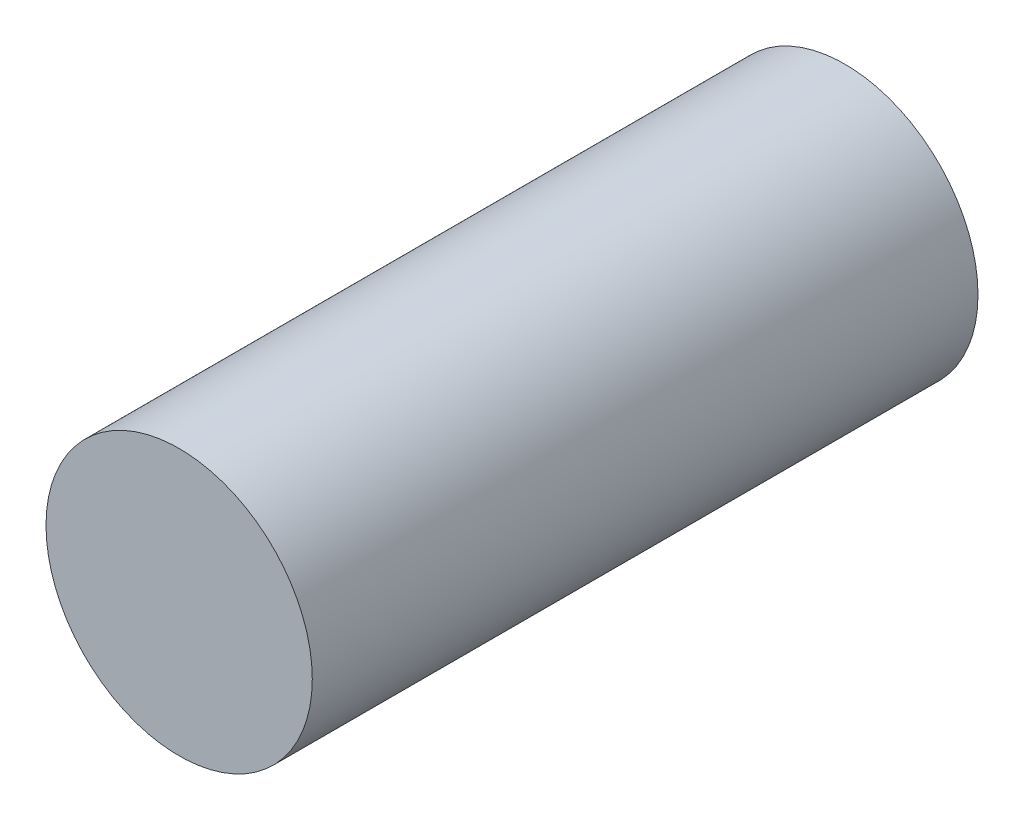
SolidWorks part; units mm, degrees
ref_plane "Plan de face" through (0, 0, 0) normal (0, 0, 1) x (1, 0, 0)
ref_plane "Plan de dessus" through (0, 0, 0) normal (0, 1, 0) x (1, 0, 0)
ref_plane "Plan de droite" through (0, 0, 0) normal (1, 0, 0) x (0, 0, -1)
sketch "Esquisse1" plane through (0, 0, 0) normal (0, 0, 1) x (1, 0, 0)
  circle A0 centre (0, 0) radius 3
  dimension "D1" = 6
extrude "Extrusion1" add sketch "Esquisse1" along normal blind 15
